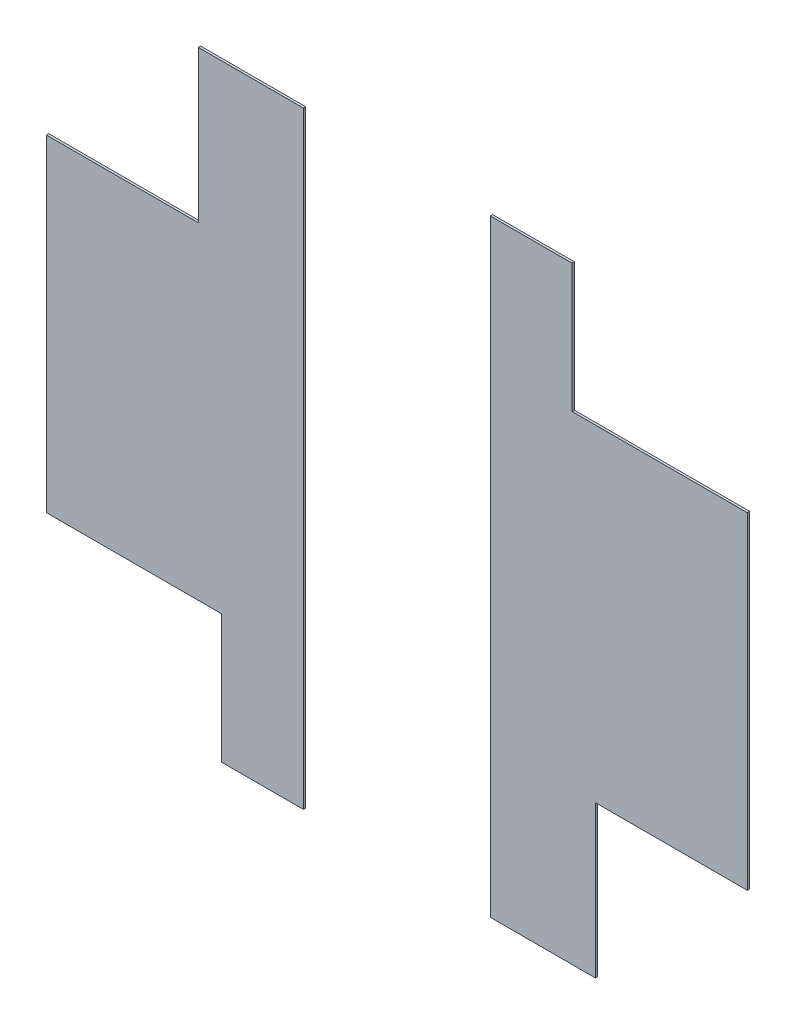
SolidWorks part; units mm, degrees
material "Alloy Steel"
ref_plane "Front" through (0, 0, 0) normal (0, 0, 1) x (1, 0, 0)
ref_plane "Top" through (0, 0, 0) normal (0, 1, 0) x (1, 0, 0)
ref_plane "Right" through (0, 0, 0) normal (1, 0, 0) x (0, 0, -1)
sketch "Sketch1" plane through (0, 0, 0) normal (0, 0, 1) x (1, 0, 0)
  line L1 (0, 0) -> (-762, 0)
  line L2 (0, 0) -> (0, 660.4)
  line L3 (0, 660.4) -> (-762, 660.4)
  line L4 (-762, 0) -> (-762, 660.4)
  dimension "D1" = 762
  dimension "D2" = 660.4
extrude "Boss-Extrude1" add sketch "Sketch1" along normal blind 2.54
sketch "Sketch2" plane through (0, 0, 2.54) normal (0, 0, 1) x (1, 0, 0)
  line L1 (-762, 660.4) -> (-596.9, 660.4)
  line L2 (-762, 660.4) -> (-762, 495.3)
  line L3 (-762, 495.3) -> (-596.9, 495.3)
  line L4 (-596.9, 660.4) -> (-596.9, 495.3)
  line L5 (0, 660.4) -> (-190.5, 660.4)
  line L6 (0, 660.4) -> (0, 520.7)
  line L7 (0, 520.7) -> (-190.5, 520.7)
  line L8 (-190.5, 660.4) -> (-190.5, 520.7)
  line L9 (0, 0) -> (-165.1, 0)
  line L10 (0, 0) -> (0, 165.1)
  line L11 (0, 165.1) -> (-165.1, 165.1)
  line L12 (-165.1, 0) -> (-165.1, 165.1)
  line L13 (-762, 0) -> (-571.5, 0)
  line L14 (-762, 0) -> (-762, 139.7)
  line L15 (-762, 139.7) -> (-571.5, 139.7)
  line L16 (-571.5, 0) -> (-571.5, 139.7)
  dimension "D1" = 190.5
  dimension "D2" = 165.1
  dimension "D3" = 139.7
  dimension "D4" = 139.7
  dimension "D5" = 190.5
extrude "Cut-Extrude1" cut sketch "Sketch2" against normal through all
sketch "Sketch3" plane through (0, 0, 2.54) normal (0, 0, 1) x (1, 0, 0)
  line L0 (0, 330.2) -> (-762, 330.2) construction
  line L1 (0, 165.1) -> (0, 520.7) construction
  line L2 (-762, 495.3) -> (-762, 139.7) construction
  line L3 (-190.5, 660.4) -> (-596.9, 660.4) construction
  line L4 (-279.4, 660.4) -> (-482.6, 660.4)
  line L5 (-279.4, 660.4) -> (-279.4, 0)
  line L6 (-279.4, 0) -> (-482.6, 0)
  line L7 (-482.6, 660.4) -> (-482.6, 0)
  line L8 (-571.5, 0) -> (-165.1, 0) construction
  line L9 (-381, 0) -> (-381, 660.4) construction
  point P6 (-381, 330.2)
  point P17 (-381, 330.2)
  dimension "D1" = 203.2
extrude "Cut-Extrude2" cut sketch "Sketch3" against normal through all
equation "\"D4@Sketch2\"=\"D3@Sketch2\""
equation "\"D5@Sketch2\"=\"D1@Sketch2\""
